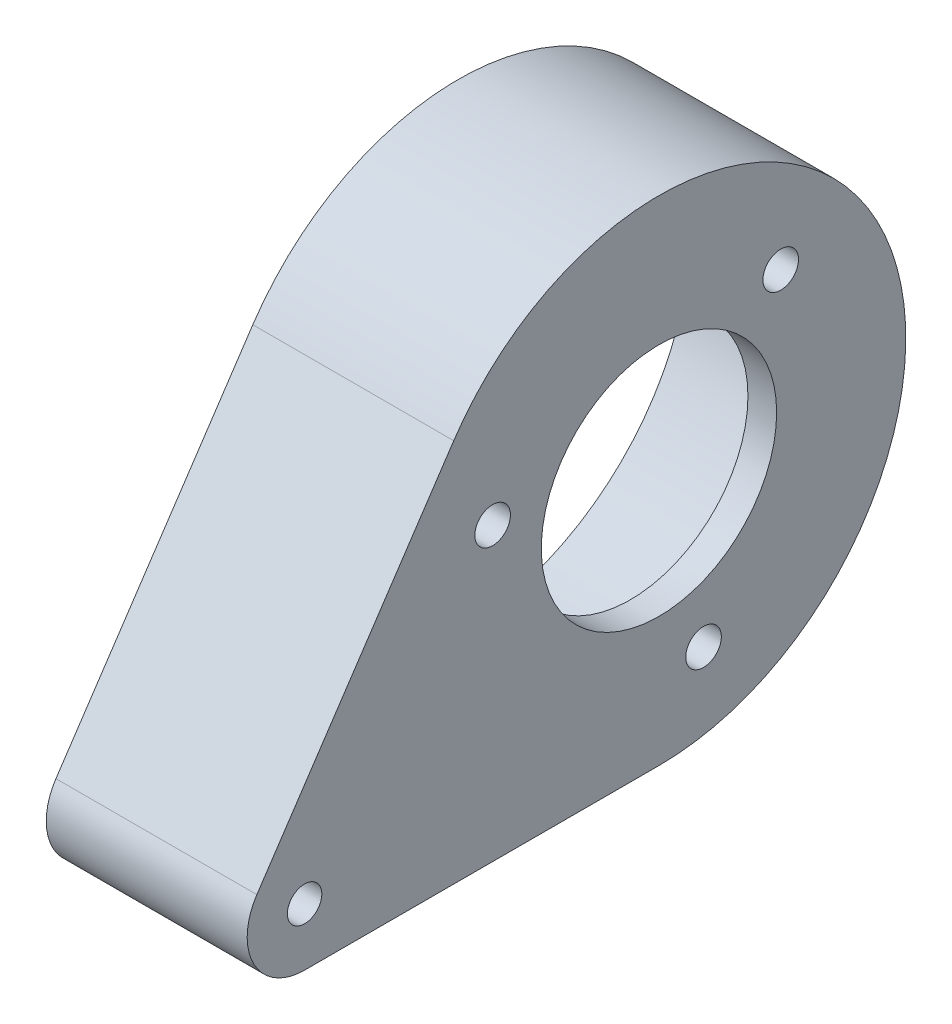
SolidWorks part; units mm, degrees
material "ABS"
ref_plane "Спереди" through (0, 0, 0) normal (0, 0, 1) x (1, 0, 0)
ref_plane "Сверху" through (0, 0, 0) normal (0, 1, 0) x (1, 0, 0)
ref_plane "Справа" through (0, 0, 0) normal (1, 0, 0) x (0, 0, -1)
sketch "Эскиз1" plane through (0, 0, 0) normal (1, 0, 0) x (0, 0, -1)
  line L0 (-30.8666, -21.5) -> (0, -21.5)
  line L1 (-30.8666, -16.5) -> (0, 0) construction
  line L2 (-35.0242, -13.7224) -> (-17.8775, 11.9435)
  arc A0 (0, -21.5) -> (-17.8775, 11.9435) centre (0, 0) ccw
  arc A1 (-35.0242, -13.7224) -> (-30.8666, -21.5) centre (-30.8666, -16.5) ccw
  dimension "D1" = 43
  dimension "D2" = 10
  dimension "D3" = 35
extrude "Бобышка-Вытянуть1" add sketch "Эскиз1" along normal blind 2.5
sketch "Эскиз2" plane through (0, 0, 0) normal (-1, 0, 0) x (0, 0, 1)
  line L0 (0, -21.5) -> (30.8666, -21.5)
  line L1 (17.8775, 11.9435) -> (35.0242, -13.7224)
  arc A0 (17.8775, 11.9435) -> (0, -21.5) centre (0, 0) ccw
  circle A1 centre (0, 0) radius 20.25
  circle A2 centre (0, 0) radius 21.5 construction
  arc A3 (30.8666, -21.5) -> (35.0242, -13.7224) centre (30.8666, -16.5) ccw
  arc A4 (30.8666, -21.5) -> (35.0242, -13.7224) centre (30.8666, -16.5) ccw construction
  dimension "D1" = 40.5
extrude "Бобышка-Вытянуть2" add sketch "Эскиз2" along normal blind 15
sketch "Эскиз3" plane through (2.5, 0, 0) normal (1, 0, 0) x (0, 0, -1)
  line L0 (0, 0) -> (0, 15) construction
  line L1 (0, 0) -> (0, -15) construction
  line L2 (0, 0) -> (10.6066, 10.6066) construction
  line L4 (0, 0) -> (-15, 0) construction
  circle A0 centre (0, 0) radius 15 construction
  circle A1 centre (10.6066, 10.6066) radius 1.55
  circle A2 centre (3.8823, -14.4889) radius 1.55
  circle A3 centre (-14.4889, 3.8823) radius 1.55
  circle A4 centre (0, 0) radius 10.25
  point P13 (0, 0)
  dimension "D1" = 30
  dimension "D2" = 3.1
  dimension "D5" = 20.5
  dimension "D4" = 135
  dimension "D3" = 3
extrude "Вырез-Вытянуть1" cut sketch "Эскиз3" against normal up to surface (2.5 mm away) up to face at (0, 0, 20.25)
sketch "Эскиз5" plane through (-15, 0, 0) normal (-1, 0, 0) x (0, 0, 1)
  circle A0 centre (30.8666, -16.5) radius 1.5
  arc A1 (30.8666, -21.5) -> (35.0242, -13.7224) centre (30.8666, -16.5) ccw construction
  dimension "D1" = 3
extrude "Вырез-Вытянуть2" cut sketch "Эскиз5" against normal through all
sketch "Эскиз6" plane through (-15, 0, 0) normal (-1, 0, 0) x (0, 0, 1)
  line L0 (0, 0) -> (21.25, 0) construction
  line L1 (21.25, 4.5) -> (20.25, 4.5)
  line L2 (21.25, 4.5) -> (21.25, -4.5)
  line L3 (21.25, -4.5) -> (20.25, -4.5)
  line L4 (20.25, 4.5) -> (20.25, 0) construction
  line L5 (20.25, 4.5) -> (19.7437, 4.5)
  line L6 (19.7437, 4.5) -> (19.7437, -4.5)
  line L7 (19.7437, -4.5) -> (20.25, -4.5)
  line L8 (20.25, 0) -> (20.25, -4.5) construction
  circle A0 centre (0, 0) radius 20.25 construction
  dimension "D1" = 1
  dimension "D2" = 9
extrude "Вырез-Вытянуть3" cut sketch "Эскиз6" against normal offset from surface (11 mm away) 4 up to face at (0, 3.8823, 12.9389)
